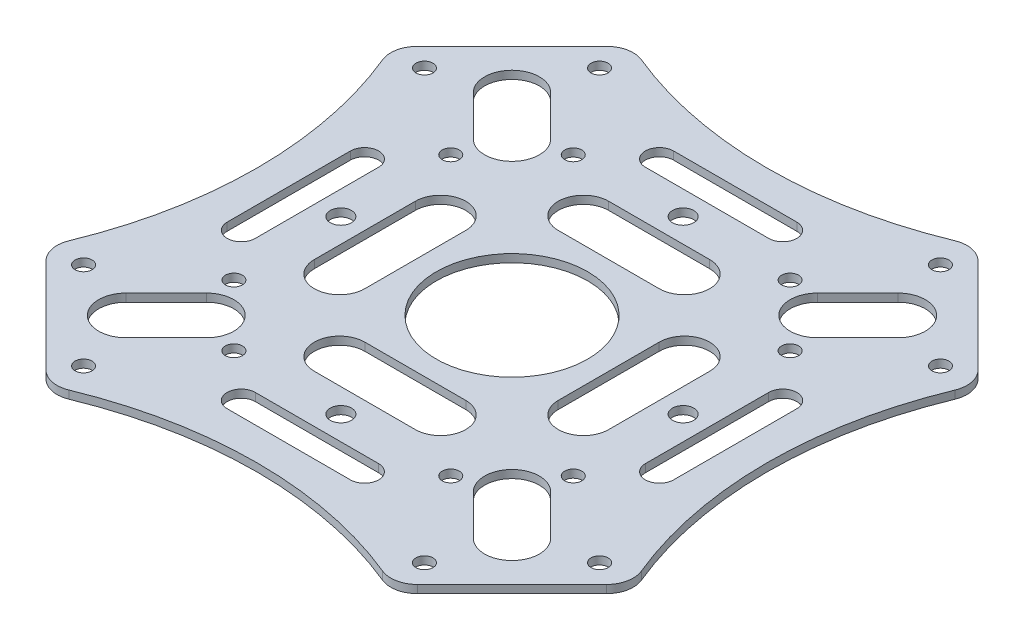
SolidWorks part; units mm, degrees
ref_plane "Front Plane" through (0, 0, 0) normal (0, 0, 1) x (1, 0, 0)
ref_plane "Top Plane" through (0, 0, 0) normal (0, 1, 0) x (1, 0, 0)
ref_plane "Right Plane" through (0, 0, 0) normal (1, 0, 0) x (0, 0, -1)
sketch "Sketch1" plane through (0, 0, 0) normal (0, 1, 0) x (1, 0, 0)
  line L0 (9.5, -27.7) -> (-9.5, -27.7)
  line L1 (-9.5, -18.2) -> (9.5, -18.2)
  line L2 (11.6, -42) -> (-11.6, -42)
  line L3 (-11.6, -36.7) -> (11.6, -36.7)
  line L4 (32.3855, -25.1023) -> (39.9515, -32.6683)
  line L5 (32.6683, -39.9515) -> (25.1023, -32.3855)
  line L6 (-9.5, 27.7) -> (9.5, 27.7)
  line L7 (9.5, 18.2) -> (-9.5, 18.2)
  line L8 (-11.6, 42) -> (11.6, 42)
  line L9 (11.6, 36.7) -> (-11.6, 36.7)
  line L10 (-32.3855, 25.1023) -> (-39.9515, 32.6683)
  line L11 (-32.6683, 39.9515) -> (-25.1023, 32.3855)
  line L12 (25.1023, 32.3855) -> (32.6683, 39.9515)
  line L13 (39.9515, 32.6683) -> (32.3855, 25.1023)
  line L14 (-34.9373, 52.7439) -> (-52.7439, 34.9373)
  line L15 (-52.7439, -34.9373) -> (-34.9373, -52.7439)
  line L16 (34.9373, -52.7439) -> (52.7439, -34.9373)
  line L17 (52.7439, 34.9373) -> (34.9373, 52.7439)
  line L18 (-25.1023, -32.3855) -> (-32.6683, -39.9515)
  line L19 (-39.9515, -32.6683) -> (-32.3855, -25.1023)
  line L20 (-42, -11.6) -> (-42, 11.6)
  line L21 (-36.7, 11.6) -> (-36.7, -11.6)
  line L22 (-27.7, -9.5) -> (-27.7, 9.5)
  line L23 (-18.2, 9.5) -> (-18.2, -9.5)
  line L24 (42, 11.6) -> (42, -11.6)
  line L25 (36.7, -11.6) -> (36.7, 11.6)
  line L26 (27.7, 9.5) -> (27.7, -9.5)
  line L27 (18.2, -9.5) -> (18.2, 9.5)
  circle A0 centre (0, 0) radius 14.25
  arc A1 (-9.5, -27.7) -> (-9.5, -18.2) centre (-9.5, -22.95) cw
  arc A2 (9.5, -18.2) -> (9.5, -27.7) centre (9.5, -22.95) cw
  arc A3 (-11.6, -42) -> (-11.6, -36.7) centre (-11.6, -39.35) cw
  arc A4 (11.6, -36.7) -> (11.6, -42) centre (11.6, -39.35) cw
  arc A5 (39.9515, -32.6683) -> (32.6683, -39.9515) centre (36.3099, -36.3099) cw
  arc A6 (25.1023, -32.3855) -> (32.3855, -25.1023) centre (28.7439, -28.7439) cw
  circle A7 centre (-32.2, 0) radius 2
  arc A8 (9.5, 27.7) -> (9.5, 18.2) centre (9.5, 22.95) cw
  arc A9 (-9.5, 18.2) -> (-9.5, 27.7) centre (-9.5, 22.95) cw
  arc A10 (11.6, 42) -> (11.6, 36.7) centre (11.6, 39.35) cw
  arc A11 (-11.6, 36.7) -> (-11.6, 42) centre (-11.6, 39.35) cw
  arc A12 (-39.9515, 32.6683) -> (-32.6683, 39.9515) centre (-36.3099, 36.3099) cw
  arc A13 (-25.1023, 32.3855) -> (-32.3855, 25.1023) centre (-28.7439, 28.7439) cw
  arc A14 (32.6683, 39.9515) -> (39.9515, 32.6683) centre (36.3099, 36.3099) cw
  arc A15 (32.3855, 25.1023) -> (25.1023, 32.3855) centre (28.7439, 28.7439) cw
  circle A16 centre (-20.4, 31.9259) radius 1.6
  circle A17 centre (-32.0673, 48.5429) radius 1.6
  circle A18 centre (-31.9259, -20.4) radius 1.6
  circle A19 centre (-48.5429, -32.0673) radius 1.6
  circle A20 centre (20.4, -31.9259) radius 1.6
  circle A21 centre (32.0673, -48.5429) radius 1.6
  circle A22 centre (31.9259, 20.4) radius 1.6
  circle A23 centre (48.5429, 32.0673) radius 1.6
  arc A24 (-52.7439, 34.9373) -> (-53.8322, 29.4991) centre (-49.2084, 31.4018) ccw
  arc A25 (-53.8322, 29.4991) -> (-53.8322, -29.4991) centre (-125.5184, 0) cw
  arc A26 (-53.8322, -29.4991) -> (-52.7439, -34.9373) centre (-49.2084, -31.4018) ccw
  arc A27 (-34.9373, -52.7439) -> (-29.4991, -53.8322) centre (-31.4018, -49.2084) ccw
  arc A28 (-29.4991, -53.8322) -> (29.4991, -53.8322) centre (0, -125.5184) cw
  arc A29 (29.4991, -53.8322) -> (34.9373, -52.7439) centre (31.4018, -49.2084) ccw
  arc A30 (52.7439, -34.9373) -> (53.8322, -29.4991) centre (49.2084, -31.4018) ccw
  arc A31 (53.8322, -29.4991) -> (53.8322, 29.4991) centre (125.5184, 0) cw
  arc A32 (53.8322, 29.4991) -> (52.7439, 34.9373) centre (49.2084, 31.4018) ccw
  arc A33 (34.9373, 52.7439) -> (29.4991, 53.8322) centre (31.4018, 49.2084) ccw
  arc A34 (29.4991, 53.8322) -> (-29.4991, 53.8322) centre (0, 125.5184) cw
  arc A35 (-29.4991, 53.8322) -> (-34.9373, 52.7439) centre (-31.4018, 49.2084) ccw
  circle A36 centre (32.0673, 48.5429) radius 1.6
  circle A37 centre (20.4, 31.9259) radius 1.6
  circle A38 centre (48.5429, -32.0673) radius 1.6
  circle A39 centre (31.9259, -20.4) radius 1.6
  circle A40 centre (-32.0673, -48.5429) radius 1.6
  circle A41 centre (-20.4, -31.9259) radius 1.6
  circle A42 centre (-48.5429, 32.0673) radius 1.6
  circle A43 centre (-31.9259, 20.4) radius 1.6
  circle A44 centre (0, 32.2) radius 2
  arc A45 (-32.6683, -39.9515) -> (-39.9515, -32.6683) centre (-36.3099, -36.3099) cw
  arc A46 (-32.3855, -25.1023) -> (-25.1023, -32.3855) centre (-28.7439, -28.7439) cw
  arc A47 (-42, 11.6) -> (-36.7, 11.6) centre (-39.35, 11.6) cw
  arc A48 (-36.7, -11.6) -> (-42, -11.6) centre (-39.35, -11.6) cw
  arc A49 (-27.7, 9.5) -> (-18.2, 9.5) centre (-22.95, 9.5) cw
  arc A50 (-18.2, -9.5) -> (-27.7, -9.5) centre (-22.95, -9.5) cw
  circle A51 centre (0, -32.2) radius 2
  arc A52 (42, -11.6) -> (36.7, -11.6) centre (39.35, -11.6) cw
  arc A53 (36.7, 11.6) -> (42, 11.6) centre (39.35, 11.6) cw
  arc A54 (27.7, -9.5) -> (18.2, -9.5) centre (22.95, -9.5) cw
  arc A55 (18.2, 9.5) -> (27.7, 9.5) centre (22.95, 9.5) cw
  circle A56 centre (32.2, 0) radius 2
  point P143 (0, 0)
extrude "Boss-Extrude1" add sketch "Sketch1" against normal mid plane 1.5
